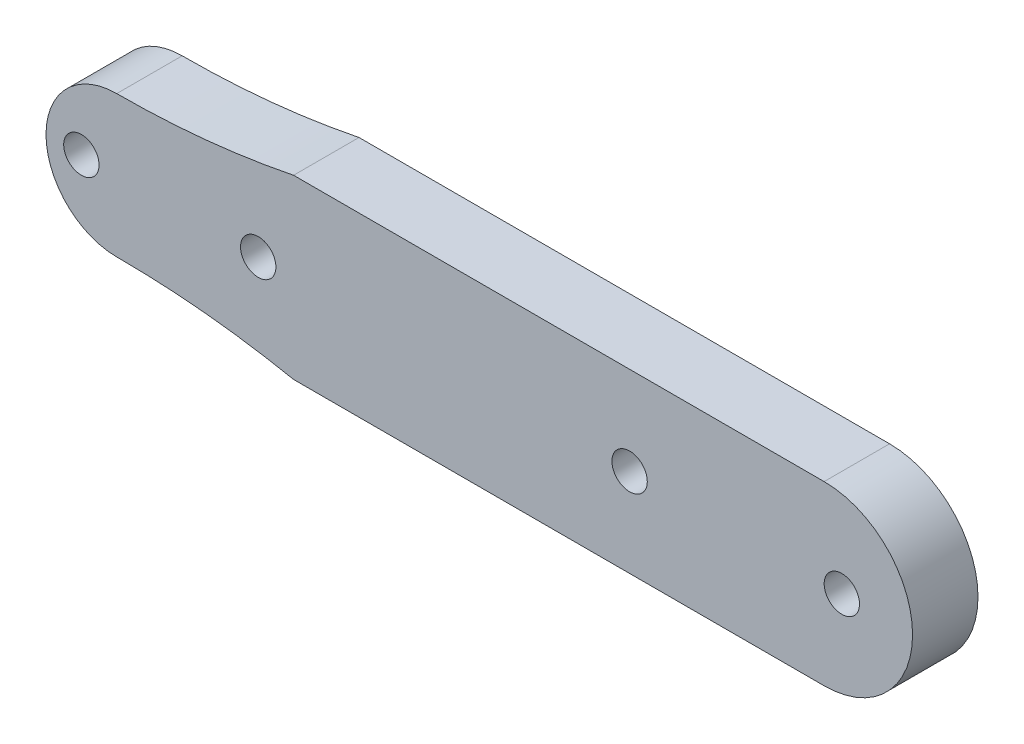
SolidWorks part; units mm, degrees
ref_plane "Front Plane" through (0, 0, 0) normal (0, 0, 1) x (1, 0, 0)
ref_plane "Top Plane" through (0, 0, 0) normal (0, 1, 0) x (1, 0, 0)
ref_plane "Right Plane" through (0, 0, 0) normal (1, 0, 0) x (0, 0, -1)
sketch "Sketch1" plane through (0, 0, 0) normal (0, 0, 1) x (1, 0, 0)
  line L0 (0, 0) -> (30, 0) construction
  line L1 (0, 5) -> (30, 5)
  line L2 (0, -5) -> (30, -5)
  line L3 (0, 0) -> (-10, 0) construction
  arc A1 (30, -5) -> (30, 5) centre (30, 0) ccw
  arc A3 (-10, 4) -> (-10, -4) centre (-10, 0) ccw
  arc A4 (-10, 4) -> (0, 5) centre (-10, 54.5) ccw
  arc A5 (-10, -4) -> (0, -5) centre (-10, -54.5) cw
  circle A6 centre (-12, 0) radius 1
  circle A7 centre (-2, 0) radius 1
  circle A8 centre (19, 0) radius 1
  circle A9 centre (31, 0) radius 1
  point P3 (15, 0)
  point P10 (-5, 0)
  point P13 (-14, 0)
  point P23 (35, 0)
  dimension "D4" = 50.5
  dimension "D5" = 50.5
  dimension "D8" = 15
  dimension "D9" = 25
  dimension "D11" = 4
  dimension "D12" = 5
  dimension "D14" = 2
  dimension "D15" = 2
  dimension "D1" = 30
  dimension "D2" = 10
  dimension "D3" = 10
  dimension "D6" = 25
  dimension "D7" = 20
  dimension "D10" = 5
  dimension "D13" = 5
  dimension "D16" = 10
  dimension "D17" = 21
  dimension "D18" = 12
  dimension "D19" = 2
  dimension "D20" = 4
extrude "Boss-Extrude1" add sketch "Sketch1" along normal blind 3.7
